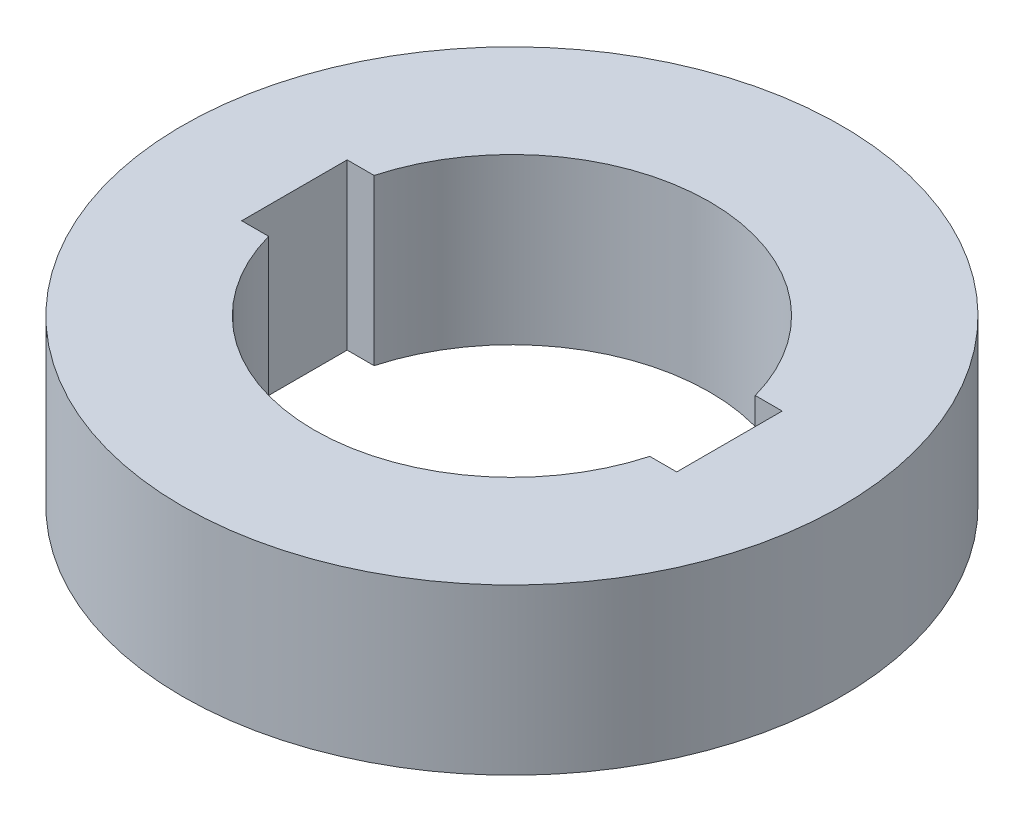
SolidWorks part; units mm, degrees
ref_plane "Front Plane" through (0, 0, 0) normal (0, 0, 1) x (1, 0, 0)
ref_plane "Top Plane" through (0, 0, 0) normal (0, 1, 0) x (1, 0, 0)
ref_plane "Right Plane" through (0, 0, 0) normal (1, 0, 0) x (0, 0, -1)
sketch "Sketch1" plane through (0, 0, 0) normal (0, 1, 0) x (1, 0, 0)
  circle A0 centre (0, 0) radius 30
  circle A1 centre (0, 0) radius 50
  dimension "D1" = 100
  dimension "D2" = 60
extrude "Boss-Extrude1" add sketch "Sketch1" along normal blind 25
sketch "Sketch2" plane through (0, 25, 0) normal (0, 1, 0) x (1, 0, 0)
  line L1 (33, 8) -> (-33, 8)
  line L2 (33, 8) -> (33, -8)
  line L3 (33, -8) -> (-33, -8)
  line L4 (-33, 8) -> (-33, -8)
  line L5 (33, 8) -> (-33, -8) construction
  line L6 (33, -8) -> (-33, 8) construction
  point P0 (0, 0)
  dimension "D1" = 16
  dimension "D2" = 66
extrude "Cut-Extrude1" cut sketch "Sketch2" against normal through all
